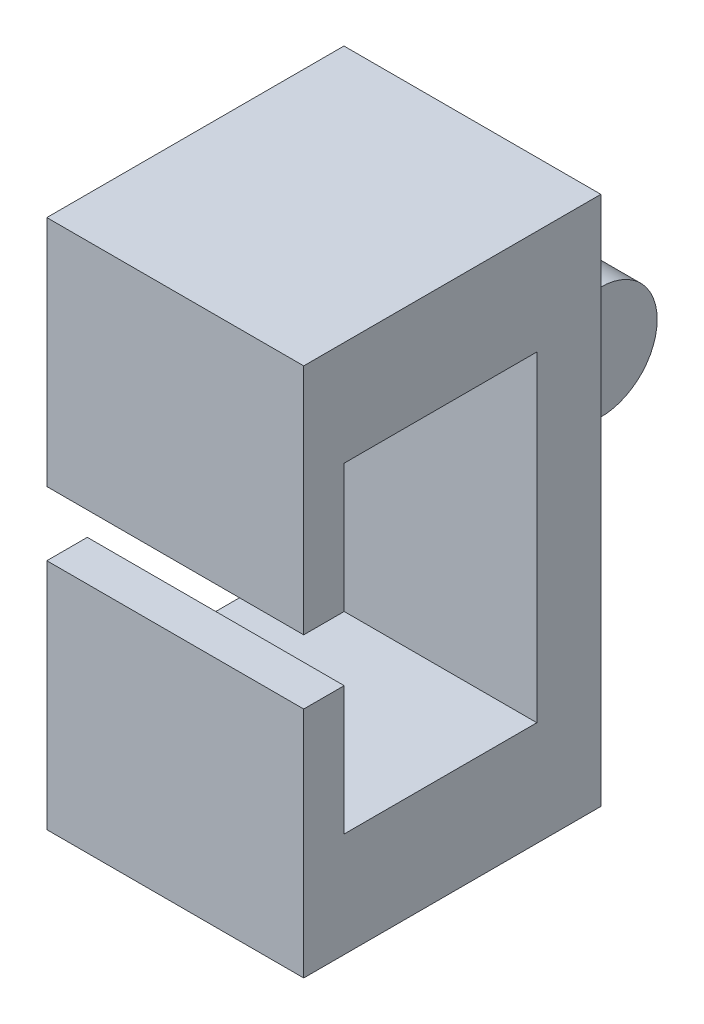
SolidWorks part; units mm, degrees
material "ASTM A36 Steel"
ref_plane "Front Plane" through (0, 0, 0) normal (1, 0, 0) x (0, 1, 0)
ref_plane "Top Plane" through (0, 0, 0) normal (0, 0, 1) x (0, 1, 0)
ref_plane "Right Plane" through (0, 0, 0) normal (0, 1, 0) x (-1, 0, 0)
sketch "Sketch1" plane through (0, 0, 0) normal (1, 0, 0) x (0, 1, 0)
  circle A0 centre (0, 0) radius 11.1361
  dimension "D1" = 22.2722
extrude "Boss-Extrude1" add sketch "Sketch1" along normal blind 25.4 contours A0
sketch "Sketch2" plane through (0, 0, 0) normal (-1, 0, 0) x (0, -1, 0)
  line L0 (12.2497, 0) -> (-12.2497, 0) construction
  line L1 (-11.1361, 0) -> (11.1252, 0)
  line L2 (-11.1361, 0) -> (-11.1361, 25.4)
  line L3 (-11.1361, 25.4) -> (11.1252, 25.4)
  line L4 (11.1252, 0) -> (11.1252, 25.4)
  circle A0 centre (0, 0) radius 11.1361 construction
  dimension "D1" = 25.4
extrude "Boss-Extrude2" add sketch "Sketch2" against normal blind 3.8346 contours L2 L3 L4 L1
sketch "Sketch3" plane through (0, 0, 0) normal (1, 0, 0) x (0, 1, 0)
  line L0 (0, -13.97) -> (0, 13.97) construction
  line L1 (-31.75, 25.4) -> (31.75, 25.4)
  line L2 (-31.75, 25.4) -> (-31.75, 38.0545)
  line L3 (-31.75, 38.0545) -> (31.75, 38.0545)
  line L4 (31.75, 25.4) -> (31.75, 38.0545)
  line L5 (11.1361, 25.4) -> (-11.1252, 25.4) construction
  point P4 (0, 25.4)
  dimension "D1" = 63.5
  dimension "D2" = 12.6545
extrude "Boss-Extrude3" add sketch "Sketch3" along normal blind 50.8
sketch "Sketch4" plane through (0, 0, 0) normal (1, 0, 0) x (0, 1, 0)
  line L0 (31.75, 38.0545) -> (-31.75, 38.0545) construction
  line L1 (-31.75, 25.4) -> (-52.4147, 25.4)
  line L2 (-31.75, 25.4) -> (-31.75, 76.1545)
  line L3 (-31.75, 76.1545) -> (-52.4147, 76.1545)
  line L4 (-52.4147, 25.4) -> (-52.4147, 76.1545)
  line L5 (31.75, 25.4) -> (52.4147, 25.4)
  line L6 (31.75, 25.4) -> (31.75, 76.1545)
  line L7 (31.75, 76.1545) -> (52.4147, 76.1545)
  line L8 (52.4147, 25.4) -> (52.4147, 76.1545)
  dimension "D1" = 20.6647
  dimension "D2" = 38.1
extrude "Boss-Extrude4" add sketch "Sketch4" along normal blind 50.8
sketch "Sketch5" plane through (0, 0, 0) normal (1, 0, 0) x (0, 1, 0)
  line L1 (-52.4147, 76.1545) -> (-6.35, 76.1545)
  line L2 (-52.4147, 76.1545) -> (-52.4147, 84.1579)
  line L3 (-52.4147, 84.1579) -> (-6.35, 84.1579)
  line L4 (-6.35, 76.1545) -> (-6.35, 84.1579)
  line L5 (52.4147, 76.1545) -> (6.35, 76.1545)
  line L6 (52.4147, 76.1545) -> (52.4147, 84.1579)
  line L7 (52.4147, 84.1579) -> (6.35, 84.1579)
  line L8 (6.35, 76.1545) -> (6.35, 84.1579)
  dimension "D1" = 8.0034
  dimension "D2" = 25.4
  dimension "D3" = 12.7
extrude "Boss-Extrude5" add sketch "Sketch5" along normal blind 50.8
equation "\"SAFETY_FAC\"= 4'Given Safety Factor"
equation "\"LOAD\"= 600'Chosen Applied Load (lbf)"
equation "\"LENGTH_A\"= 1in'Chosen Length for Feature A (in)"
equation "\"STRENGTH\"= 36259.4'ASTM A36 Steel Yield Strenght (psi)"
equation "\"DIAMETER_A\"= 2 * ( ( 4 * \"SAFETY_FAC\" * \"LOAD\" * \"LENGTH_A\" ) / ( PI * \"STRENGTH\" ) ) ^ ( 1 / 3 )'Calculated Diameter of Feature A (in)"
equation "\"THICKNESS_B\"= ( \"LOAD\" * 8 ) / ( \"STRENGTH\" * \"DIAMETER_A\" )'Calculated Thickness of Feature B (in)"
equation "\"LENGTH_C\"= 2.5'Found Length based on Given Rigid T-beam Dimensions (in)"
equation "\"PRIMARY_THICKNESS\"= 2'Chosen Thickness of the primary section (in_"
equation "\"HEIGHT_C\"= ( ( 3 * \"LOAD\" * \"LENGTH_C\" * \"SAFETY_FAC\" ) / ( \"PRIMARY_THICKNESS\" * \"STRENGTH\" ) ) ^ ( 1 / 2 )'Calculated Height of Feature C (in)"
equation "\"LOAD_DISTANCE_D\"= \"LENGTH_C\" / 2'Calculated Distance of Load Applied to Feature D (in)"
equation "\"HEIGHT_D\"= 1.5'Found Height based on the GIven Rigid T-beam Dimensions (in)"
equation "\"LENGTH_D\"= ( ( 12 * \"LOAD\" * \"LOAD_DISTANCE_D\" * \"SAFETY_FAC\" ) / ( \"HEIGHT_D\" * \"STRENGTH\" ) ) ^ ( 1 / 2 )'Calculated Length of Feature D (in)"
equation "\"LENGTH_E\"= 1'Found Length for Feature E on given Rigid T-Beam Dimensions (in)"
equation "\"HEIGHT_E\"= ( ( 3 * \"LENGTH_E\" * \"LOAD\" * \"SAFETY_FAC\" ) / ( \"PRIMARY_THICKNESS\" * \"STRENGTH\" ) ) ^ ( 1 / 2 )'Calculated height of Feature E (in)"
equation "\"D1@Sketch1\"=\"DIAMETER_A\""
equation "\"D1@Boss-Extrude1\"=\"LENGTH_A\""
equation "\"D1@Boss-Extrude2\"=\"THICKNESS_B\""
equation "\"D1@Sketch3\"=\"LENGTH_C\""
equation "\"D2@Sketch3\"=\"HEIGHT_C\""
equation "\"D1@Boss-Extrude3\"=\"PRIMARY_THICKNESS\""
equation "\"D2@Sketch4\"=\"HEIGHT_D\""
equation "\"D1@Sketch4\"=\"LENGTH_D\""
equation "\"D1@Boss-Extrude4\"=\"PRIMARY_THICKNESS\""
equation "\"D1@Sketch5\"=\"HEIGHT_E\""
equation "\"D2@Sketch5\"=\"LENGTH_E\""
equation "\"D1@Boss-Extrude5\"=\"PRIMARY_THICKNESS\""
